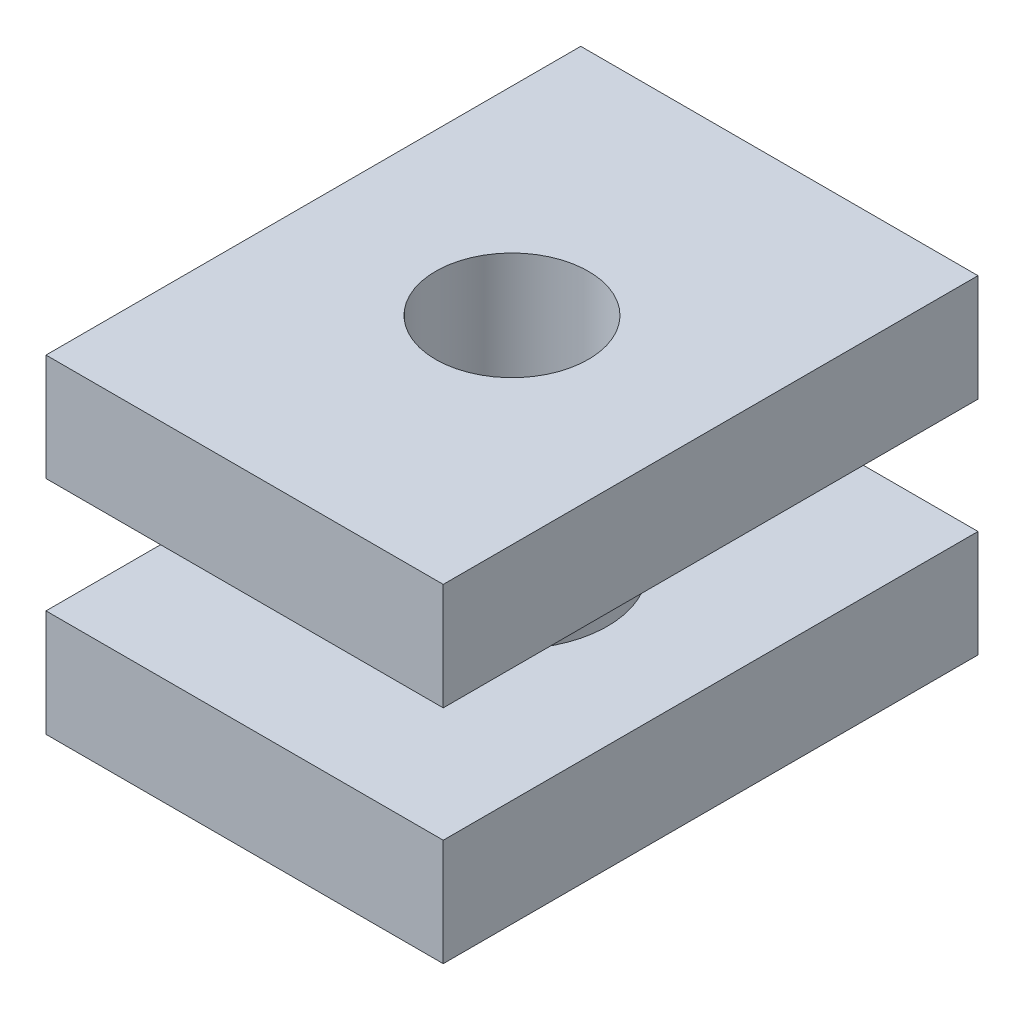
SolidWorks part; units mm, degrees
material "BUTYL"
ref_plane "Front Plane" through (0, 0, 0) normal (0, 0, 1) x (1, 0, 0)
ref_plane "Top Plane" through (0, 0, 0) normal (0, 1, 0) x (1, 0, 0)
ref_plane "Right Plane" through (0, 0, 0) normal (1, 0, 0) x (0, 0, -1)
sketch "Sketch1" plane through (0, 0, 0) normal (0, 1, 0) x (1, 0, 0)
  line L1 (-3.302, -4.445) -> (3.302, -4.445)
  line L2 (-3.302, -4.445) -> (-3.302, 4.445)
  line L3 (-3.302, 4.445) -> (3.302, 4.445)
  line L4 (3.302, -4.445) -> (3.302, 4.445)
  line L5 (-3.302, -4.445) -> (3.302, 4.445) construction
  line L6 (-3.302, 4.445) -> (3.302, -4.445) construction
  point P0 (0, 0)
  dimension "D1" = 6.604
  dimension "D2" = 8.89
sketch "Sketch3" plane through (0, 0, 0) normal (0, 1, 0) x (1, 0, 0)
  line L0 (-3.302, 4.445) -> (3.302, -4.445) construction
  circle A0 centre (0, 0) radius 1.5875
  dimension "D1" = 3.175
extrude "Boss-Extrude2" add sketch "Sketch3" along normal mid plane 5.461
sketch "Sketch4" plane through (0, -2.7305, 0) normal (0, -1, 0) x (1, 0, 0)
  line L0 (-3.302, 4.445) -> (-3.302, -4.445) construction
  line L1 (-3.302, 4.445) -> (3.302, 4.445) construction
  line L2 (3.302, 4.445) -> (3.302, -4.445) construction
  line L3 (-3.302, -4.445) -> (3.302, -4.445) construction
  line L4 (-3.302, 4.445) -> (-3.302, -4.445)
  line L5 (-3.302, 4.445) -> (3.302, 4.445)
  line L6 (3.302, 4.445) -> (3.302, -4.445)
  line L7 (-3.302, -4.445) -> (3.302, -4.445)
extrude "Boss-Extrude3" add sketch "Sketch4" against normal blind 1.778
sketch "Sketch5" plane through (0, 2.7305, 0) normal (0, 1, 0) x (1, 0, 0)
  line L0 (3.302, -4.445) -> (3.302, 4.445) construction
  line L1 (-3.302, -4.445) -> (3.302, -4.445) construction
  line L2 (-3.302, -4.445) -> (-3.302, 4.445) construction
  line L3 (-3.302, 4.445) -> (3.302, 4.445) construction
  line L4 (3.302, -4.445) -> (3.302, 4.445)
  line L5 (-3.302, -4.445) -> (3.302, -4.445)
  line L6 (-3.302, -4.445) -> (-3.302, 4.445)
  line L7 (-3.302, 4.445) -> (3.302, 4.445)
extrude "Boss-Extrude4" add sketch "Sketch5" against normal blind 1.778
sketch "Sketch6" plane through (0, 2.7305, 0) normal (0, 1, 0) x (1, 0, 0)
  circle A0 centre (0, 0) radius 1.27
  dimension "D1" = 2.54
extrude "Cut-Extrude1" cut sketch "Sketch6" against normal through all
